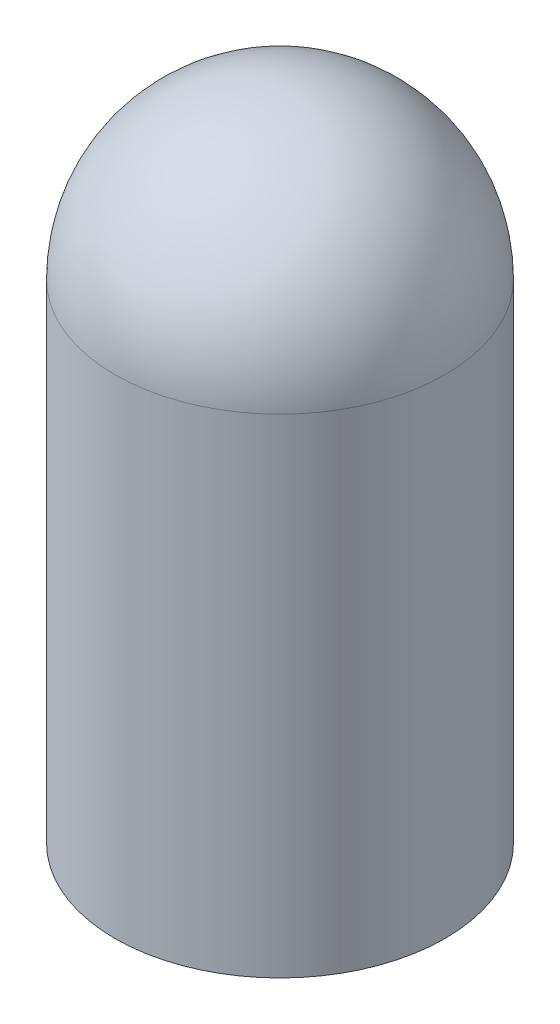
SolidWorks part; units mm, degrees
ref_plane "Front Plane" through (0, 0, 0) normal (0, 0, 1) x (1, 0, 0)
ref_plane "Top Plane" through (0, 0, 0) normal (0, 1, 0) x (1, 0, 0)
ref_plane "Right Plane" through (0, 0, 0) normal (1, 0, 0) x (0, 0, -1)
sketch "Sketch1" plane through (0, 0, 0) normal (0, 1, 0) x (1, 0, 0)
  circle A0 centre (0, 0) radius 2.35
  dimension "D1" = 4.7
extrude "Boss-Extrude1" add sketch "Sketch1" along normal blind 6.95
sketch "Sketch2" plane through (0, 0, 0) normal (0, 0, 1) x (1, 0, 0)
  line L0 (0, 6.95) -> (0, 9.3)
  line L1 (2.35, 6.95) -> (-2.35, 6.95) construction
  line L2 (2.35, 6.95) -> (0, 6.95)
  arc A0 (0, 9.3) -> (2.35, 6.95) centre (0, 6.95) cw
  dimension "D1" = 2.35
revolve "Revolve1" add sketch "Sketch2" angle 360 about L0
